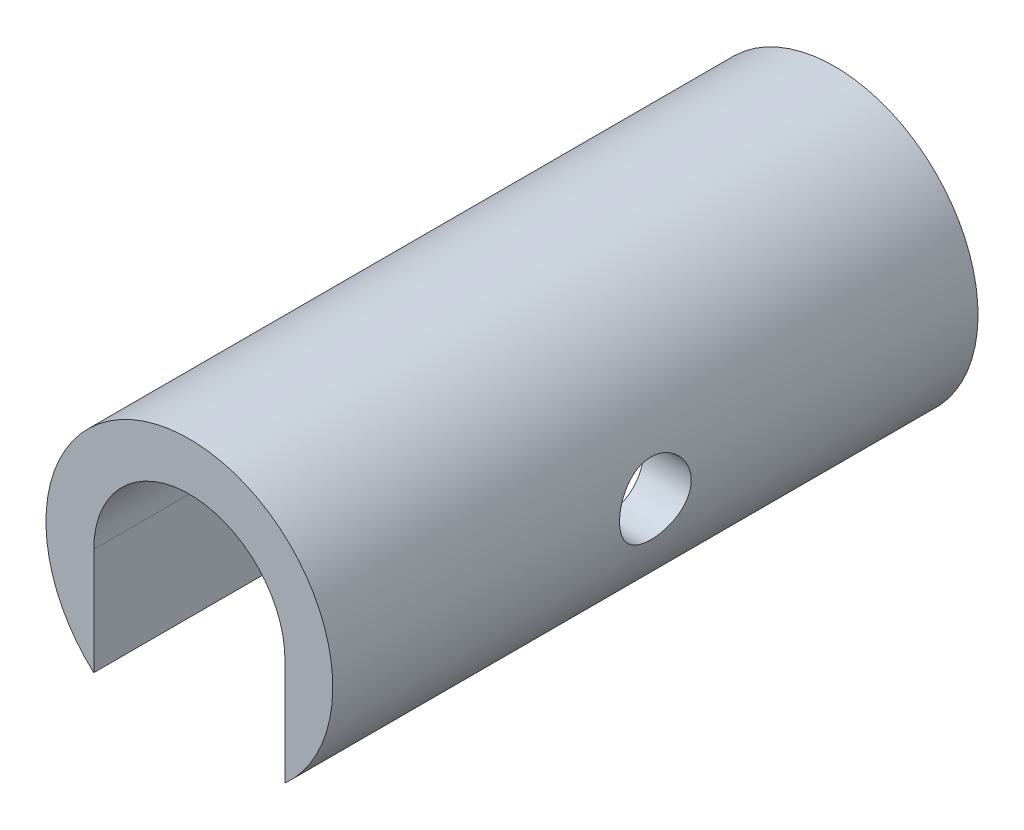
SolidWorks part; units mm, degrees
ref_plane "Alzado" through (0, 0, 0) normal (1, 0, 0) x (0, 1, 0)
ref_plane "Planta" through (0, 0, 0) normal (0, 0, 1) x (0, 1, 0)
ref_plane "Vista lateral" through (0, 0, 0) normal (0, 1, 0) x (-1, 0, 0)
sketch "Croquis1" plane through (0, 0, 0) normal (0, 0, 1) x (0, 1, 0)
  line L0 (0, 4) -> (-4.4721, 4)
  line L1 (0, -4) -> (-4.4721, -4)
  arc A0 (0, -4) -> (0, 4) centre (0, 0) ccw
  arc A1 (-4.4721, -4) -> (-4.4721, 4) centre (0, 0) ccw
  dimension "D1" = 8
  dimension "D2" = 12
extrude "Saliente-Extruir1" add sketch "Croquis1" along normal blind 27 contours A0 L0 A1 L1
sketch "Croquis2" plane through (0, 0, 0) normal (1, 0, 0) x (0, 1, 0)
  line L0 (0, 0) -> (0, 27) construction
  line L1 (6, 27) -> (-4.4721, 27) construction
  circle A0 centre (0, 13.5) radius 1.5
  dimension "D1" = 3
extrude "Cortar-Extruir1" cut sketch "Croquis2" against normal mid plane 27
